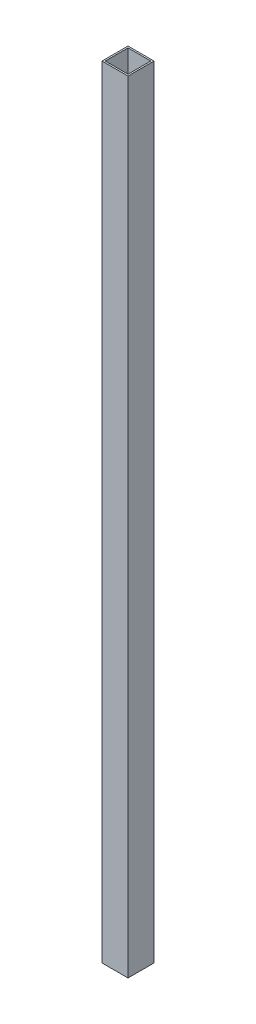
SolidWorks part; units mm, degrees
ref_plane "Front Plane" through (0, 0, 0) normal (0, 0, 1) x (1, 0, 0)
ref_plane "Top Plane" through (0, 0, 0) normal (0, 1, 0) x (1, 0, 0)
ref_plane "Right Plane" through (0, 0, 0) normal (1, 0, 0) x (0, 0, -1)
sketch "Sketch1" plane through (0, 0, 0) normal (0, 1, 0) x (1, 0, 0)
  line L1 (0, 0) -> (25.4, 0)
  line L2 (0, 0) -> (0, 25.4)
  line L3 (0, 25.4) -> (25.4, 25.4)
  line L4 (25.4, 0) -> (25.4, 25.4)
  line L5 (1.5875, 23.8125) -> (23.8125, 23.8125)
  line L6 (1.5875, 23.8125) -> (1.5875, 1.5875)
  line L7 (1.5875, 1.5875) -> (23.8125, 1.5875)
  line L8 (23.8125, 23.8125) -> (23.8125, 1.5875)
  point P9 (1.5875, 12.7)
  point P10 (12.7, 23.8125)
  point P11 (23.8125, 12.7)
  dimension "D1" = 25.4
  dimension "D2" = 25.4
  dimension "D3" = 1.5875
  dimension "D4" = 1.5875
  dimension "D5" = 1.5875
  dimension "D6" = 1.5875
extrude "Boss-Extrude1" add sketch "Sketch1" along normal blind 762
